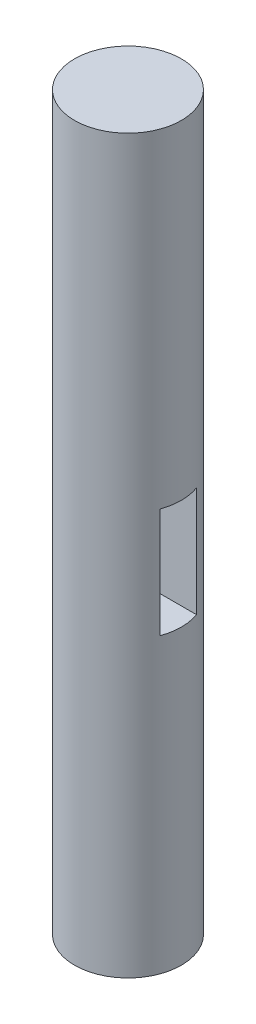
SolidWorks part; units mm, degrees
ref_plane "Front Plane" through (0, 0, 0) normal (0, 0, 1) x (1, 0, 0)
ref_plane "Top Plane" through (0, 0, 0) normal (0, 1, 0) x (1, 0, 0)
ref_plane "Right Plane" through (0, 0, 0) normal (1, 0, 0) x (0, 0, -1)
sketch "Sketch1" plane through (0, 0, 0) normal (0, 1, 0) x (1, 0, 0)
  circle A0 centre (0, 0) radius 9.271
  dimension "D1" = 18.542
extrude "Boss-Extrude1" add sketch "Sketch1" along normal blind 127
sketch "Sketch2" plane through (0, 0, 0) normal (1, 0, 0) x (0, 0, -1)
  line L1 (-3.175, 50.8406) -> (3.175, 50.8406)
  line L2 (-3.175, 50.8406) -> (-3.175, 69.8906)
  line L3 (-3.175, 69.8906) -> (3.175, 69.8906)
  line L4 (3.175, 50.8406) -> (3.175, 69.8906)
  line L5 (-3.175, 61.2809) -> (0, 61.2809) construction
  line L6 (0, 10.1981) -> (0, -10.1981) construction
  line L7 (0, 61.2809) -> (3.175, 61.2809) construction
  line L8 (10.1981, 0) -> (-10.1981, 0) construction
  dimension "D1" = 50.8406
  dimension "D2" = 19.05
  dimension "D3" = 6.35
extrude "Cut-Extrude1" cut sketch "Sketch2" against normal through all both and the other way through all
